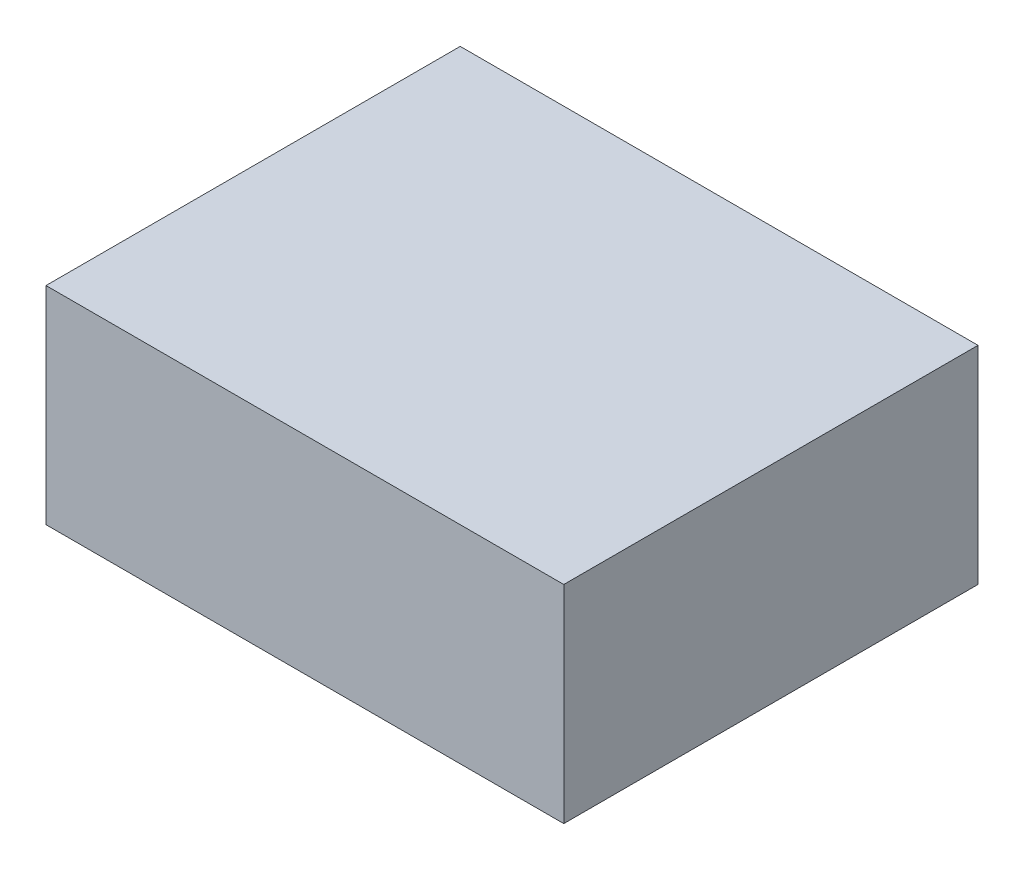
SolidWorks part; units mm, degrees
ref_plane "Front Plane" through (0, 0, 0) normal (0, 0, 1) x (1, 0, 0)
ref_plane "Top Plane" through (0, 0, 0) normal (0, 1, 0) x (1, 0, 0)
ref_plane "Right Plane" through (0, 0, 0) normal (1, 0, 0) x (0, 0, -1)
sketch "Sketch1" plane through (0, 0, 0) normal (0, 0, 1) x (1, 0, 0)
  line L1 (0, 0) -> (95.25, 0)
  line L2 (0, 0) -> (0, 38.1)
  line L3 (0, 38.1) -> (95.25, 38.1)
  line L4 (95.25, 0) -> (95.25, 38.1)
  dimension "D1" = 38.1
  dimension "D2" = 95.25
extrude "Boss-Extrude1" add sketch "Sketch1" along normal blind 76.2
